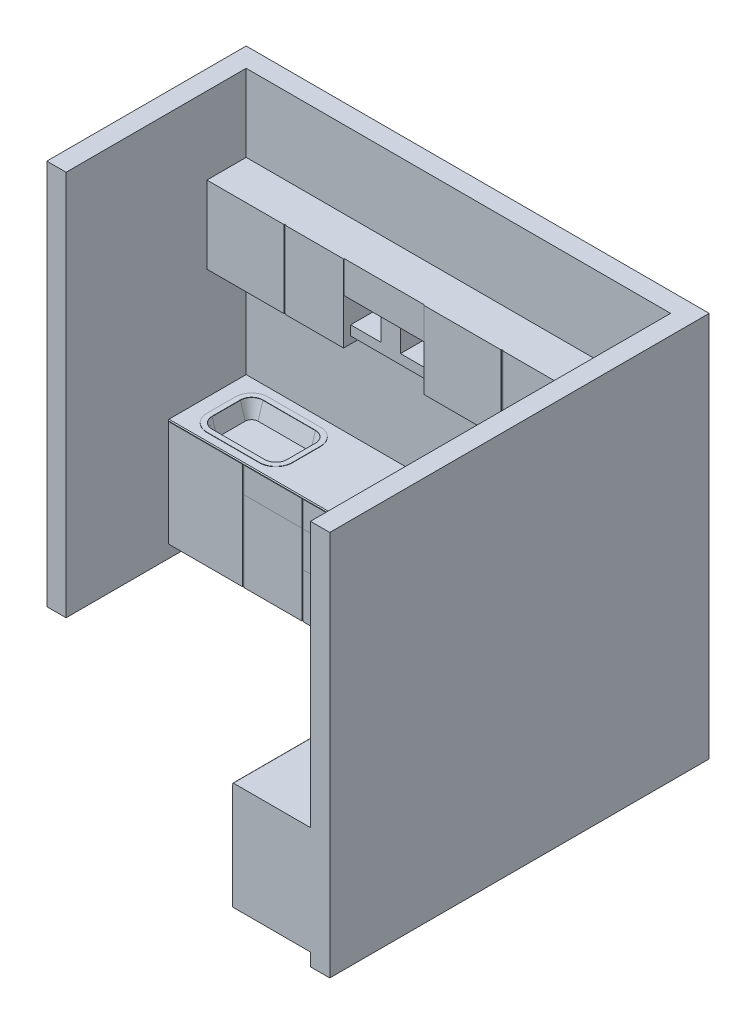
SolidWorks part; units mm, degrees
ref_plane "Front Plane" through (0, 0, 0) normal (0, 0, 1) x (1, 0, 0)
ref_plane "Top Plane" through (0, 0, 0) normal (0, 1, 0) x (1, 0, 0)
ref_plane "Right Plane" through (0, 0, 0) normal (1, 0, 0) x (0, 0, -1)
sketch "Sketch1" plane through (0, 0, 0) normal (0, 1, 0) x (1, 0, 0)
  line L0 (-1828.8, 0) -> (-1828.8, 1574.8)
  line L1 (-1828.8, 1574.8) -> (1828.8, 1574.8)
  line L2 (-1676.4, 0) -> (-1676.4, 1422.4)
  line L3 (-1676.4, 1422.4) -> (1676.4, 1422.4)
  line L4 (1676.4, -1422.4) -> (1676.4, 1422.4)
  line L5 (1828.8, -1422.4) -> (1828.8, 1574.8)
  line L6 (-1828.8, 0) -> (-1676.4, 0)
  line L7 (1828.8, -1422.4) -> (1676.4, -1422.4)
  point P0 (0, 0)
  dimension "D1" = 3352.8
  dimension "D2" = 2844.8
  dimension "D3" = 152.4
extrude "Boss-Extrude1" add sketch "Sketch1" along normal blind 3048
sketch "Sketch2" plane through (0, 0, 0) normal (0, 1, 0) x (1, 0, 0)
  line L0 (-1676.4, 1422.4) -> (1676.4, 1422.4) construction
  line L1 (1676.4, 1422.4) -> (1676.4, -1422.4) construction
  line L2 (-1676.4, 0) -> (-1676.4, 1422.4) construction
  line L3 (1676.4, 1422.4) -> (1676.4, -1422.4)
  line L4 (-1676.4, 812.8) -> (-1676.4, 1422.4)
  line L5 (-1676.4, 1422.4) -> (1676.4, 1422.4)
  line L6 (-1066.8, 812.8) -> (1066.8, 812.8) construction
  line L7 (-1676.4, 812.8) -> (1066.8, 812.8)
  line L8 (1066.8, 812.8) -> (1066.8, -1422.4)
  line L9 (-1066.8, 0) -> (-1066.8, 812.8) construction
  line L10 (-1676.4, 0) -> (-1676.4, 1422.4) construction
  line L11 (1066.8, -1422.4) -> (1676.4, -1422.4)
  dimension "D1" = 609.6
extrude "Boss-Extrude2" add sketch "Sketch2" along normal blind 838.2 from offset 101.6 separate body
sketch "Sketch3" plane through (0, 939.8, 0) normal (0, 1, 0) x (1, 0, 0)
  line L0 (1066.8, 812.8) -> (1066.8, -1422.4) construction
  line L1 (1066.8, 812.8) -> (1066.8, -1422.4)
  line L2 (-1676.4, 812.8) -> (1066.8, 812.8) construction
  line L3 (-1676.4, 812.8) -> (1066.8, 812.8)
sketch "Sketch4" plane through (0, 0, 1422.4) normal (0, 0, 1) x (1, 0, 0)
  line L1 (1676.4, 939.8) -> (1066.8, 939.8)
  line L2 (1676.4, 939.8) -> (1676.4, 952.5)
  line L3 (1676.4, 952.5) -> (1066.8, 952.5)
  arc A0 (1066.8, 952.5) -> (1066.8, 939.8) centre (1068.6604, 946.15) ccw
sweep "Sweep2" add profiles "Sketch4" path "Sketch3"
sketch "Sketch5" plane through (0, 0, -812.8) normal (0, 0, 1) x (1, 0, 0)
  line L0 (-1092.2, 939.8) -> (-1092.2, 101.6)
  line L1 (-1079.5, 939.8) -> (-1079.5, 101.6)
  line L2 (-622.3, 939.8) -> (-622.3, 101.6)
  line L3 (-609.6, 939.8) -> (-609.6, 101.6)
  line L4 (-1676.4, 101.6) -> (1066.8, 101.6)
  line L5 (1066.8, 101.6) -> (1066.8, 939.8)
  line L6 (1066.8, 939.8) -> (-1676.4, 939.8)
  line L7 (-1676.4, 939.8) -> (-1676.4, 101.6)
  line L8 (-1676.4, 101.6) -> (-1092.2, 101.6)
  line L9 (1066.8, 101.6) -> (1066.8, 939.8)
  line L10 (1066.8, 939.8) -> (457.2, 939.8)
  line L11 (-1676.4, 939.8) -> (-1676.4, 101.6)
  line L12 (0, 939.8) -> (0, 101.6)
  line L13 (12.7, 939.8) -> (12.7, 101.6)
  line L14 (444.5, 939.8) -> (444.5, 101.6)
  line L15 (457.2, 939.8) -> (457.2, 101.6)
  line L16 (-1092.2, 939.8) -> (-1676.4, 939.8)
  line L17 (-622.3, 939.8) -> (-1079.5, 939.8)
  line L18 (0, 939.8) -> (-609.6, 939.8)
  line L19 (444.5, 939.8) -> (12.7, 939.8)
  line L20 (457.2, 101.6) -> (1066.8, 101.6)
  line L21 (12.7, 101.6) -> (444.5, 101.6)
  line L22 (-609.6, 101.6) -> (0, 101.6)
  line L23 (-1079.5, 101.6) -> (-622.3, 101.6)
  dimension "D1" = 0
  dimension "D2" = 584.2
  dimension "D3" = 12.7
  dimension "D4" = 457.2
  dimension "D5" = 12.7
  dimension "D6" = 609.6
  dimension "D7" = 12.7
  dimension "D8" = 431.8
  dimension "D9" = 12.7
extrude "Boss-Extrude3" add sketch "Sketch5" along normal blind 5.08
sketch "Sketch6" plane through (0, 0, -807.72) normal (0, 0, 1) x (1, 0, 0)
  line L0 (-1079.5, 736.6) -> (-622.3, 736.6)
  line L1 (-1079.5, 939.8) -> (-1079.5, 101.6) construction
  line L2 (-622.3, 101.6) -> (-622.3, 939.8) construction
  line L3 (-622.3, 939.8) -> (-1079.5, 939.8) construction
  dimension "D1" = 203.2
split line "Split Line1"
sketch "Sketch7" plane through (0, 0, -807.72) normal (0, 0, 1) x (1, 0, 0)
  line L0 (-609.6, 736.6) -> (0, 736.6)
  line L1 (-609.6, 939.8) -> (-609.6, 101.6) construction
  line L2 (0, 101.6) -> (0, 939.8) construction
  line L3 (0, 939.8) -> (-609.6, 939.8) construction
  dimension "D1" = 203.2
split line "Split Line2"
sketch "Sketch8" plane through (0, 0, -807.72) normal (0, 0, 1) x (1, 0, 0)
  line L0 (-609.6, 457.2) -> (0, 457.2)
  line L1 (-609.6, 736.6) -> (-609.6, 101.6) construction
  line L2 (0, 101.6) -> (0, 736.6) construction
  line L3 (0, 736.6) -> (-609.6, 736.6) construction
  dimension "D1" = 279.4
split line "Split Line3"
sketch "Sketch9" plane through (0, 0, -807.72) normal (0, 0, 1) x (1, 0, 0)
  line L0 (12.7, 457.2) -> (444.5, 457.2)
  line L1 (12.7, 939.8) -> (12.7, 101.6) construction
  line L2 (444.5, 101.6) -> (444.5, 939.8) construction
  line L3 (444.5, 939.8) -> (12.7, 939.8) construction
  dimension "D1" = 482.6
split line "Split Line4"
sketch "Sketch10" plane through (1066.8, 0, 0) normal (-1, 0, 0) x (0, 0, 1)
  line L0 (-350.52, 939.8) -> (-350.52, 101.6)
  line L1 (-337.82, 939.8) -> (-337.82, 101.6)
  line L2 (-185.42, 939.8) -> (-185.42, 101.6)
  line L3 (-172.72, 939.8) -> (-172.72, 101.6)
  line L4 (1422.4, 939.8) -> (-807.72, 939.8)
  line L5 (-807.72, 939.8) -> (-807.72, 101.6)
  line L6 (-807.72, 101.6) -> (1422.4, 101.6)
  line L7 (1422.4, 101.6) -> (1422.4, 939.8)
  line L8 (1422.4, 939.8) -> (906.78, 939.8)
  line L9 (-807.72, 939.8) -> (-807.72, 101.6)
  line L10 (-807.72, 101.6) -> (-350.52, 101.6)
  line L11 (1422.4, 101.6) -> (1422.4, 939.8)
  line L12 (436.88, 939.8) -> (436.88, 101.6)
  line L13 (424.18, 939.8) -> (424.18, 101.6)
  line L14 (894.08, 939.8) -> (894.08, 101.6)
  line L15 (906.78, 939.8) -> (906.78, 101.6)
  line L16 (-350.52, 939.8) -> (-807.72, 939.8)
  line L17 (-185.42, 939.8) -> (-337.82, 939.8)
  line L18 (424.18, 939.8) -> (-172.72, 939.8)
  line L19 (894.08, 939.8) -> (436.88, 939.8)
  line L20 (906.78, 101.6) -> (1422.4, 101.6)
  line L21 (436.88, 101.6) -> (894.08, 101.6)
  line L22 (-172.72, 101.6) -> (424.18, 101.6)
  line L23 (-337.82, 101.6) -> (-185.42, 101.6)
  dimension "D1" = 0
  dimension "D2" = 457.2
  dimension "D3" = 12.7
  dimension "D4" = 152.4
  dimension "D5" = 12.7
  dimension "D6" = 609.6
  dimension "D7" = 12.7
  dimension "D8" = 457.2
  dimension "D9" = 12.7
extrude "Boss-Extrude4" add sketch "Sketch10" along normal blind 5.08
sketch "Sketch11" plane through (0, 0, 0) normal (0, 1, 0) x (1, 0, 0)
  line L0 (1676.4, 1422.4) -> (1676.4, -1422.4) construction
  line L1 (-1676.4, 1422.4) -> (1676.4, 1422.4) construction
  line L2 (-1676.4, 0) -> (-1676.4, 1422.4) construction
  line L3 (1676.4, 1422.4) -> (1676.4, -1422.4)
  line L4 (-1676.4, 1422.4) -> (1676.4, 1422.4)
  line L5 (-1676.4, 1117.6) -> (-1676.4, 1422.4)
  line L6 (-1371.6, 1117.6) -> (1371.6, 1117.6) construction
  line L7 (-1676.4, 1117.6) -> (1371.6, 1117.6)
  line L8 (1371.6, 1117.6) -> (1371.6, -1422.4)
  line L9 (-1371.6, 0) -> (-1371.6, 1117.6) construction
  line L10 (-1676.4, 0) -> (-1676.4, 1422.4) construction
  line L11 (1371.6, -1422.4) -> (1676.4, -1422.4)
  dimension "D1" = 304.8
extrude "Boss-Extrude5" add sketch "Sketch11" along normal blind 609.6 from offset 1828.8
sketch "Sketch12" plane through (0, 0, -1117.6) normal (0, 0, 1) x (1, 0, 0)
  line L0 (-1066.8, 2438.4) -> (-1066.8, 1828.8)
  line L1 (-1054.1, 2438.4) -> (-1054.1, 1828.8)
  line L2 (-596.9, 2438.4) -> (-596.9, 1828.8)
  line L3 (38.1, 2438.4) -> (38.1, 1828.8)
  line L4 (-1676.4, 1828.8) -> (1371.6, 1828.8)
  line L5 (1371.6, 1828.8) -> (1371.6, 2438.4)
  line L6 (1371.6, 2438.4) -> (-1676.4, 2438.4)
  line L7 (-1676.4, 2438.4) -> (-1676.4, 1828.8)
  line L8 (-1676.4, 1828.8) -> (-1066.8, 1828.8)
  line L9 (1371.6, 1828.8) -> (1371.6, 2438.4)
  line L10 (1371.6, 2438.4) -> (660.4, 2438.4)
  line L11 (-1676.4, 2438.4) -> (-1676.4, 1828.8)
  line L12 (647.7, 2438.4) -> (647.7, 1828.8)
  line L13 (660.4, 2438.4) -> (660.4, 1828.8)
  line L14 (-1066.8, 2438.4) -> (-1676.4, 2438.4)
  line L15 (-1054.1, 1828.8) -> (-596.9, 1828.8)
  line L16 (647.7, 2438.4) -> (38.1, 2438.4)
  line L17 (660.4, 1828.8) -> (1371.6, 1828.8)
  line L18 (-596.9, 2438.4) -> (-1054.1, 2438.4)
  line L19 (38.1, 1828.8) -> (647.7, 1828.8)
  dimension "D1" = 0
  dimension "D2" = 609.6
  dimension "D3" = 12.7
  dimension "D4" = 457.2
  dimension "D5" = 635
  dimension "D6" = 609.6
  dimension "D7" = 12.7
extrude "Boss-Extrude6" add sketch "Sketch12" along normal blind 5.08
sketch "Sketch13" plane through (0, 0, -1117.6) normal (0, 0, 1) x (1, 0, 0)
  line L0 (38.1, 2438.4) -> (38.1, 1828.8) construction
  line L1 (-596.9, 1828.8) -> (38.1, 1828.8)
  line L2 (-596.9, 1828.8) -> (-596.9, 2184.8969)
  line L3 (-596.9, 2184.8969) -> (38.1, 2184.8969)
  line L4 (38.1, 1828.8) -> (38.1, 2184.8969)
extrude "Cut-Extrude2" cut sketch "Sketch13" against normal blind 304.8
sketch "Sketch14" plane through (0, 0, -1422.4) normal (0, 0, 1) x (1, 0, 0)
  line L0 (-355.6, 2184.8969) -> (-203.2, 2184.8969)
  line L2 (-355.6, 2184.8969) -> (-355.6, 1959.907)
  line L3 (-203.2, 2184.8969) -> (-203.2, 1959.907)
  line L4 (-596.9, 1959.907) -> (-355.6, 1959.907)
  line L5 (-596.9, 2184.8969) -> (-596.9, 1828.8) construction
  line L6 (38.1, 2438.4) -> (38.1, 1828.8) construction
  line L7 (-596.9, 1883.707) -> (38.1, 1883.707)
  line L8 (-596.9, 1959.907) -> (-596.9, 1883.707)
  line L9 (38.1, 1883.707) -> (38.1, 1959.907)
  line L13 (-203.2, 1959.907) -> (38.1, 1959.907)
  line L14 (-596.9, 1959.907) -> (38.1, 1959.907) construction
  dimension "D3" = 76.2
extrude "Boss-Extrude7" add sketch "Sketch14" along normal blind 254 separate body
sketch "Sketch15" plane through (0, 0, 1422.4) normal (0, 0, 1) x (1, 0, 0)
  line L1 (1371.6, 1828.8) -> (1676.4, 1828.8)
  line L2 (1371.6, 1828.8) -> (1371.6, 2438.4)
  line L3 (1371.6, 2438.4) -> (1676.4, 2438.4)
  line L4 (1676.4, 1828.8) -> (1676.4, 2438.4)
extrude "Cut-Extrude3" cut sketch "Sketch15" against normal blind 2844.8
sketch "Sketch16" plane through (0, 952.5, 0) normal (0, 1, 0) x (1, 0, 0)
  line L1 (1676.4, 1422.4) -> (1066.8, 1422.4)
  line L2 (1676.4, 1422.4) -> (1676.4, 812.8)
  line L3 (1676.4, 812.8) -> (1066.8, 812.8)
  line L4 (1066.8, 1422.4) -> (1066.8, 812.8)
extrude "Cut-Extrude4" cut sketch "Sketch16" along normal blind 2844.8
sketch "Sketch17" plane through (0, 2438.4, 0) normal (0, 1, 0) x (1, 0, 0)
  line L1 (1066.8, 1422.4) -> (1676.4, 1422.4)
  line L2 (1066.8, 1422.4) -> (1066.8, 965.2)
  line L3 (1066.8, 965.2) -> (1676.4, 965.2)
  line L4 (1676.4, 1422.4) -> (1676.4, 965.2)
  dimension "D1" = 609.6
  dimension "D2" = 457.2
extrude "Boss-Extrude8" add sketch "Sketch17" against normal up to next separate body
sketch "Sketch18" plane through (0, 0, -965.2) normal (0, 0, 1) x (1, 0, 0)
  line L0 (1651, 2413) -> (1092.2, 2413)
  line L1 (1092.2, 2413) -> (1092.2, 977.9)
  line L2 (1092.2, 977.9) -> (1651, 977.9)
  line L3 (1651, 977.9) -> (1651, 2413)
extrude "Cut-Extrude5" cut sketch "Sketch18" against normal blind 406.4
sketch "Sketch19" plane through (0, 0, -1371.6) normal (0, 0, 1) x (1, 0, 0)
  line L0 (1092.2, 1695.45) -> (1651, 1695.45)
  line L1 (1092.2, 2413) -> (1092.2, 977.9) construction
  line L2 (1651, 977.9) -> (1651, 2413) construction
  line L3 (1092.2, 1379.2464) -> (1651, 1379.2464)
extrude "Extrude-Thin1" add sketch "Sketch19" along normal blind 355.6 separate body thin
sketch "Sketch20" plane through (0, 0, -1016) normal (0, 0, 1) x (1, 0, 0)
  line L1 (1092.2, 2413) -> (1651, 2413)
  line L2 (1092.2, 2413) -> (1092.2, 977.9)
  line L3 (1092.2, 977.9) -> (1651, 977.9)
  line L4 (1651, 2413) -> (1651, 977.9)
extrude "Boss-Extrude9" add sketch "Sketch20" along normal blind 25.4 from offset 25.4 separate body
sketch "Sketch21" plane through (0, 952.5, 0) normal (0, 1, 0) x (1, 0, 0)
  line L0 (-1066.8, 1112.52) -> (-1676.4, 1112.52) construction
  line L1 (-1434.9835, 911.9654) -> (-1020.2697, 911.9654)
  line L2 (-1523.8835, 1000.8654) -> (-1523.8835, 1224.1746)
  line L3 (-1434.9835, 1313.0746) -> (-1020.2697, 1313.0746)
  line L4 (-931.3697, 1000.8654) -> (-931.3697, 1224.1746)
  line L5 (-1523.8835, 911.9654) -> (-931.3697, 1313.0746) construction
  line L6 (-1523.8835, 1313.0746) -> (-931.3697, 911.9654) construction
  arc A0 (-1020.2697, 911.9654) -> (-931.3697, 1000.8654) centre (-1020.2697, 1000.8654) ccw
  arc A1 (-1523.8835, 1224.1746) -> (-1434.9835, 1313.0746) centre (-1434.9835, 1224.1746) cw
  arc A2 (-1434.9835, 911.9654) -> (-1523.8835, 1000.8654) centre (-1434.9835, 1000.8654) cw
  arc A3 (-1020.2697, 1313.0746) -> (-931.3697, 1224.1746) centre (-1020.2697, 1224.1746) cw
  point P0 (-1227.6266, 1112.52)
  dimension "D1" = 88.9
extrude "Cut-Extrude6" cut sketch "Sketch21" against normal blind 124.46 draft 17
sketch "Sketch22" plane through (0, 952.5, 0) normal (0, 1, 0) x (1, 0, 0)
  line L1 (-931.3697, 1000.8654) -> (-931.3697, 1224.1746) construction
  line L2 (-1523.8835, 1224.1746) -> (-1523.8835, 1000.8654) construction
  line L3 (-1020.2697, 1313.0746) -> (-1434.9835, 1313.0746) construction
  line L4 (-1434.9835, 871.3254) -> (-1020.2697, 871.3254)
  line L5 (-931.3697, 1000.8654) -> (-931.3697, 1224.1746)
  line L6 (-1523.8835, 1224.1746) -> (-1523.8835, 1000.8654)
  line L7 (-1020.2697, 1313.0746) -> (-1434.9835, 1313.0746)
  line L8 (-890.7297, 1000.8654) -> (-890.7297, 1224.1746)
  line L9 (-1020.2697, 1353.7146) -> (-1434.9835, 1353.7146)
  line L10 (-1564.5235, 1224.1746) -> (-1564.5235, 1000.8654)
  line L11 (-1020.2697, 911.9654) -> (-1434.9835, 911.9654)
  arc A0 (-1523.8835, 1000.8654) -> (-1434.9835, 911.9654) centre (-1434.9835, 1000.8654) ccw construction
  arc A1 (-1020.2697, 911.9654) -> (-931.3697, 1000.8654) centre (-1020.2697, 1000.8654) ccw construction
  arc A2 (-931.3697, 1224.1746) -> (-1020.2697, 1313.0746) centre (-1020.2697, 1224.1746) ccw construction
  arc A3 (-1434.9835, 1313.0746) -> (-1523.8835, 1224.1746) centre (-1434.9835, 1224.1746) ccw construction
  arc A4 (-1523.8835, 1000.8654) -> (-1434.9835, 911.9654) centre (-1434.9835, 1000.8654) ccw
  arc A5 (-1020.2697, 911.9654) -> (-931.3697, 1000.8654) centre (-1020.2697, 1000.8654) ccw
  arc A6 (-931.3697, 1224.1746) -> (-1020.2697, 1313.0746) centre (-1020.2697, 1224.1746) ccw
  arc A7 (-1434.9835, 1313.0746) -> (-1523.8835, 1224.1746) centre (-1434.9835, 1224.1746) ccw
  arc A8 (-1020.2697, 871.3254) -> (-890.7297, 1000.8654) centre (-1020.2697, 1000.8654) ccw
  arc A9 (-890.7297, 1224.1746) -> (-1020.2697, 1353.7146) centre (-1020.2697, 1224.1746) ccw
  arc A10 (-1434.9835, 1353.7146) -> (-1564.5235, 1224.1746) centre (-1434.9835, 1224.1746) ccw
  arc A11 (-1564.5235, 1000.8654) -> (-1434.9835, 871.3254) centre (-1434.9835, 1000.8654) ccw
  dimension "D1" = 40.64
extrude "Boss-Extrude10" add sketch "Sketch22" along normal blind 2.54
